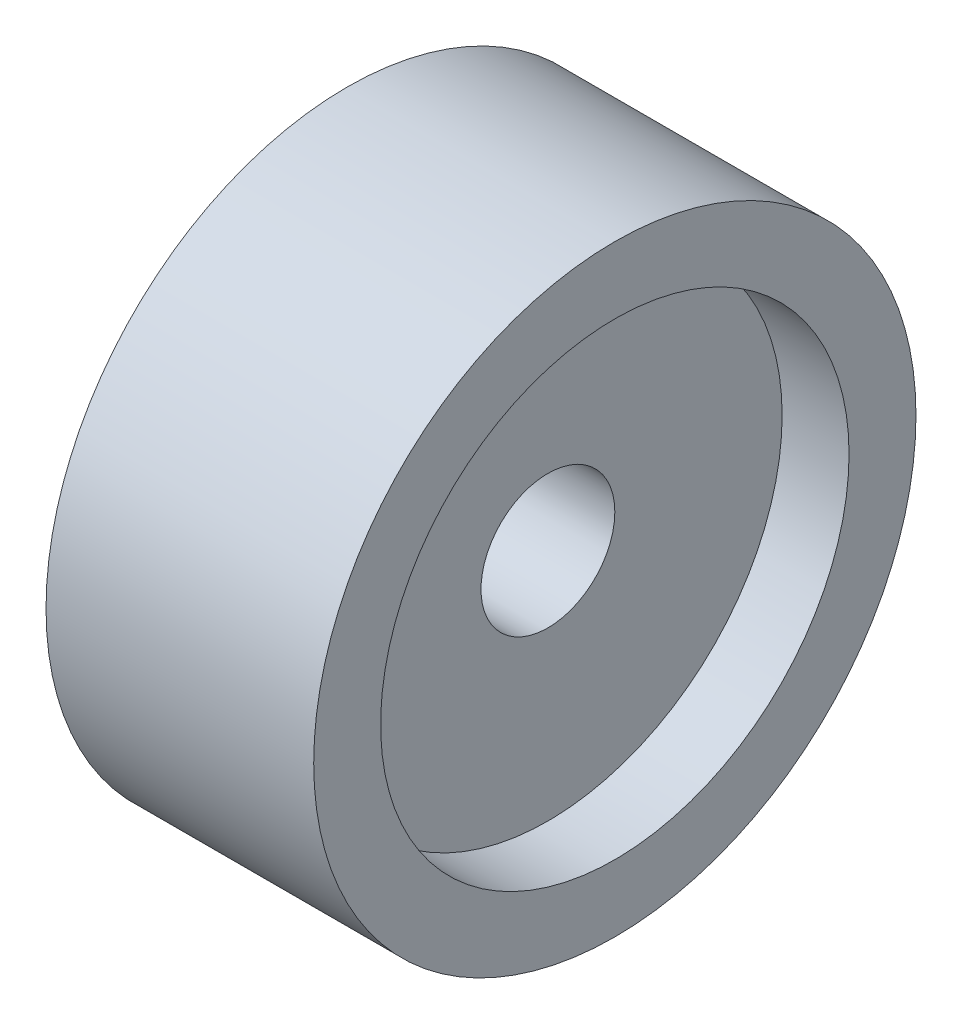
SolidWorks part; units mm, degrees
ref_plane "Front Plane" through (0, 0, 0) normal (0, 0, 1) x (1, 0, 0)
ref_plane "Top Plane" through (0, 0, 0) normal (0, 1, 0) x (1, 0, 0)
ref_plane "Right Plane" through (0, 0, 0) normal (1, 0, 0) x (0, 0, -1)
sketch "Sketch3" plane through (0, 0, 0) normal (1, 0, 0) x (0, 0, -1)
  circle A0 centre (0, 0) radius 200
  circle A1 centre (0, 0) radius 50
  dimension "D1" = 400
  dimension "D2" = 100
extrude "Boss-Extrude4" add sketch "Sketch3" along normal blind 100
sketch "Sketch4" plane through (100, 0, 0) normal (1, 0, 0) x (0, 0, -1)
  circle A0 centre (0, 0) radius 175
  circle A1 centre (0, 0) radius 225
  dimension "D1" = 350
  dimension "D2" = 450
extrude "Boss-Extrude5" add sketch "Sketch4" along normal blind 50 and the other way blind 150
